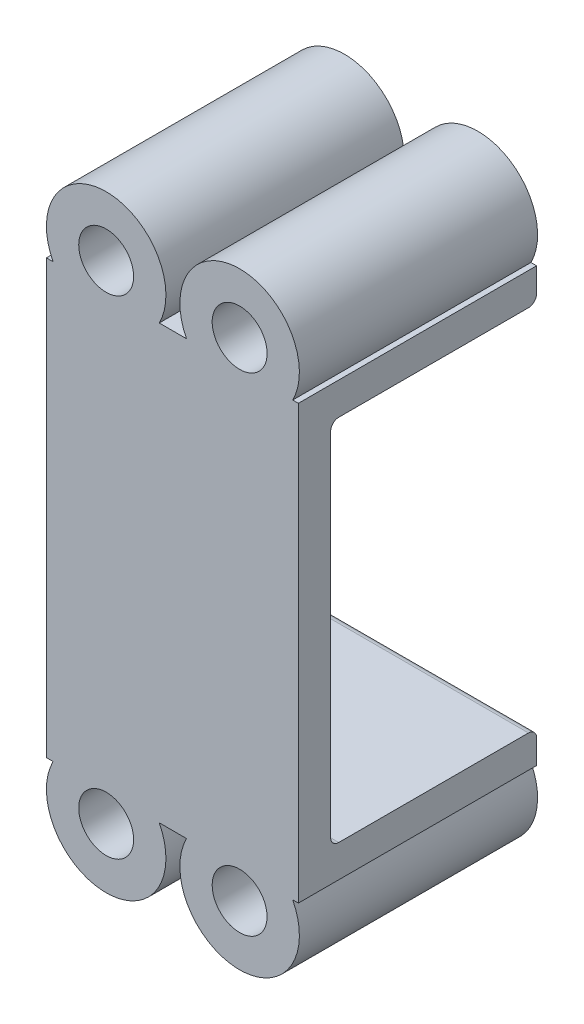
SolidWorks part; units mm, degrees
ref_plane "Piano frontale" through (0, 0, 0) normal (0, 0, 1) x (1, 0, 0)
ref_plane "Piano superiore" through (0, 0, 0) normal (0, 1, 0) x (1, 0, 0)
ref_plane "Piano destro" through (0, 0, 0) normal (1, 0, 0) x (0, 0, -1)
sketch "Schizzo1" plane through (0, 0, 0) normal (0, 0, 1) x (1, 0, 0)
  line L1 (-7.8316, 11.4) -> (7.7684, 11.4)
  line L2 (-7.8316, 11.4) -> (-7.8316, -11.4)
  line L3 (-7.8316, -11.4) -> (7.7684, -11.4)
  line L4 (7.7684, 11.4) -> (7.7684, -11.4)
  dimension "D1" = 15.6
  dimension "D2" = 22.8
extrude "Estrusione-Estrusione1" add sketch "Schizzo1" along normal blind 2
sketch "Schizzo7" plane through (0, 0, 2) normal (0, 0, 1) x (1, 0, 0)
  line L0 (0, 19.244) -> (0, -15.5575) construction
  line L1 (-15.8679, 0) -> (19.3659, 0) construction
  line L2 (7.7684, 13.4) -> (7.4179, 13.4)
  line L3 (-7.4179, 13.4) -> (-7.8316, 13.4)
  line L4 (-7.8316, 13.4) -> (-7.8316, 11.4)
  line L5 (-7.8316, 11.4) -> (7.7684, 11.4)
  line L6 (7.7684, 13.4) -> (7.7684, 11.4)
  line L7 (0.8452, 13.4) -> (-0.8452, 13.4)
  line L8 (0.8452, -13.4) -> (-0.8452, -13.4)
  line L9 (7.7684, -13.4) -> (7.7684, -11.4)
  line L10 (-7.8316, -11.4) -> (7.7684, -11.4)
  line L11 (-7.8316, -13.4) -> (-7.8316, -11.4)
  line L12 (-7.4179, -13.4) -> (-7.8316, -13.4)
  line L13 (7.7684, -13.4) -> (7.4179, -13.4)
  circle A0 centre (4.1316, 15.1) radius 1.7
  arc A1 (7.4179, 13.4) -> (0.8452, 13.4) centre (4.1316, 15.1) ccw
  circle A2 centre (-4.1316, 15.1) radius 1.7
  arc A3 (-7.4179, 13.4) -> (-0.8452, 13.4) centre (-4.1316, 15.1) cw
  arc A4 (-7.4179, -13.4) -> (-0.8452, -13.4) centre (-4.1316, -15.1) ccw
  circle A5 centre (-4.1316, -15.1) radius 1.7
  arc A6 (7.4179, -13.4) -> (0.8452, -13.4) centre (4.1316, -15.1) cw
  circle A7 centre (4.1316, -15.1) radius 1.7
  point P26 (-7.8316, 11.4)
  dimension "D1" = 3.4
  dimension "D3" = 2
  dimension "D4" = 15.6
extrude "Estrusione-Estrusione8" add sketch "Schizzo7" against normal blind 14.75
fillet "Raccordo2" radius 0.5 4 edges at (-0.0316, 11.4, -12.75) (-0.0316, -11.4, -12.75)
